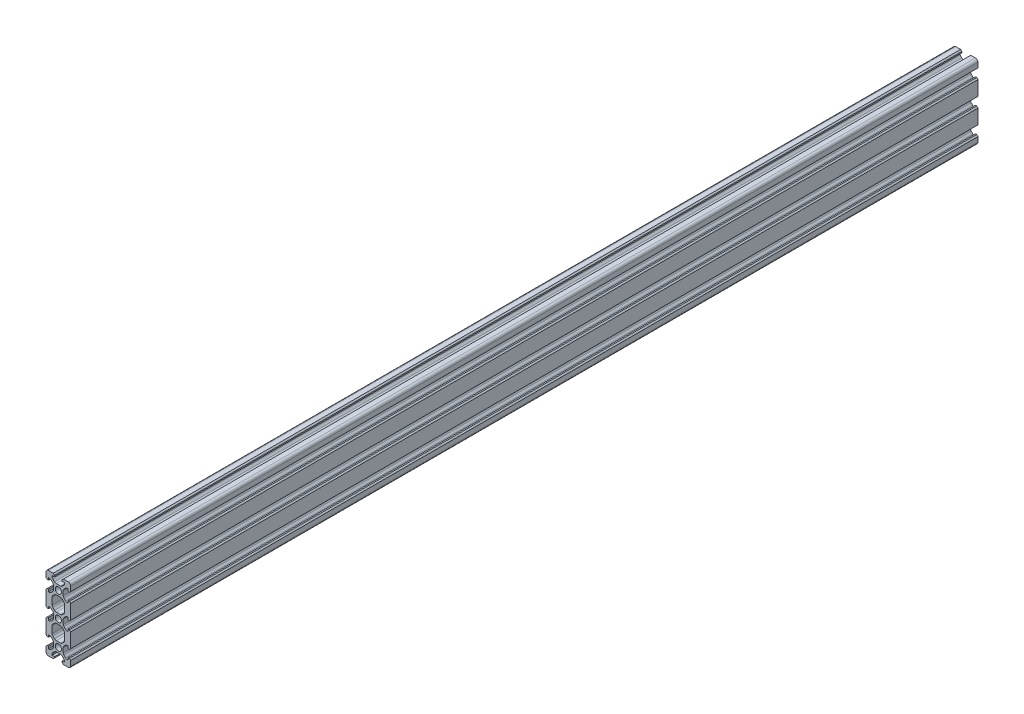
SolidWorks part; units mm, degrees
ref_plane "Front Plane" through (0, 0, 0) normal (0, 0, 1) x (1, 0, 0)
ref_plane "Top Plane" through (0, 0, 0) normal (0, 1, 0) x (1, 0, 0)
ref_plane "Right Plane" through (0, 0, 0) normal (1, 0, 0) x (0, 0, -1)
sketch "Sketch1" plane through (0, 0, 0) normal (0, 0, 1) x (1, 0, 0)
  line B0 (3.1, 29) -> (4.1, 30)
  line B1 (9, -23.1) -> (10, -24.1)
  line B2 (4.4142, -14.1716) -> (3.1236, -15.4621)
  line B3 (10, -15.9) -> (9, -16.9)
  line B4 (5.8284, -24.4142) -> (4.5379, -23.1236)
  line B5 (7.2426, -25) -> (8, -25)
  line B6 (8, -23.1) -> (8, -25)
  line B7 (7.2426, -15) -> (8, -15)
  line B8 (-1.7094, -16.0479) -> (1.7094, -16.0479)
  line B9 (8, -15) -> (8, -16.9)
  line B10 (8, -16.9) -> (9, -16.9)
  line B11 (8, -23.1) -> (9, -23.1)
  line B12 (3.9521, -18.2906) -> (3.9521, -21.7094)
  line B13 (-3.1236, -15.4621) -> (-4.4142, -14.1716)
  line B14 (10, -24.1) -> (10, -28)
  line B15 (4.5379, -16.8764) -> (5.8284, -15.5858)
  line B16 (-3.1, -29) -> (-4.1, -30)
  line B17 (8, -30) -> (4.1, -30)
  line B18 (4.1, -30) -> (3.1, -29)
  line B19 (-4.4142, -25.8284) -> (-3.1236, -24.5379)
  line B20 (-5, -27.2426) -> (-5, -28)
  line B21 (-3.1, -28) -> (-5, -28)
  line B22 (5, -27.2426) -> (5, -28)
  line B23 (5, -28) -> (3.1, -28)
  line B24 (3.1, -28) -> (3.1, -29)
  line B25 (-3.1, -28) -> (-3.1, -29)
  line B26 (1.7094, -23.9521) -> (-1.7094, -23.9521)
  line B27 (-4.1, -30) -> (-8, -30)
  line B28 (3.1236, -24.5379) -> (4.4142, -25.8284)
  line B29 (-9, -16.9) -> (-10, -15.9)
  line B30 (-10, -28) -> (-10, -24.1)
  line B31 (-10, -24.1) -> (-9, -23.1)
  line B32 (-5.8284, -15.5858) -> (-4.5379, -16.8764)
  line B33 (-7.2426, -15) -> (-8, -15)
  line B34 (-8, -16.9) -> (-8, -15)
  line B35 (-7.2426, -25) -> (-8, -25)
  line B36 (-8, -25) -> (-8, -23.1)
  line B37 (-8, -23.1) -> (-9, -23.1)
  line B38 (-8, -16.9) -> (-9, -16.9)
  line B39 (-3.9521, -21.7094) -> (-3.9521, -18.2906)
  line B40 (-4.5379, -23.1236) -> (-5.8284, -24.4142)
  circle B41 centre (0, -20) radius 2.5
  arc B42 (-4.5379, -16.8764) -> (-3.9521, -18.2906) centre (-5.9521, -18.2906) cw
  arc B43 (-5.8284, -15.5858) -> (-7.2426, -15) centre (-7.2426, -17) ccw
  arc B44 (-5, -12.7574) -> (-4.4142, -14.1716) centre (-3, -12.7574) ccw
  arc B45 (5, -12.7574) -> (4.4142, -14.1716) centre (3, -12.7574) cw
  arc B46 (7.2426, -15) -> (5.8284, -15.5858) centre (7.2426, -17) ccw
  arc B47 (5.8284, -24.4142) -> (7.2426, -25) centre (7.2426, -23) ccw
  arc B48 (5, -27.2426) -> (4.4142, -25.8284) centre (3, -27.2426) ccw
  arc B49 (-4.4142, -25.8284) -> (-5, -27.2426) centre (-3, -27.2426) ccw
  arc B50 (-7.2426, -25) -> (-5.8284, -24.4142) centre (-7.2426, -23) ccw
  arc B51 (-3.9521, -21.7094) -> (-4.5379, -23.1236) centre (-5.9521, -21.7094) cw
  arc B52 (-3.1236, -24.5379) -> (-1.7094, -23.9521) centre (-1.7094, -25.9521) cw
  arc B53 (1.7094, -23.9521) -> (3.1236, -24.5379) centre (1.7094, -25.9521) cw
  arc B54 (4.5379, -23.1236) -> (3.9521, -21.7094) centre (5.9521, -21.7094) cw
  arc B55 (3.9521, -18.2906) -> (4.5379, -16.8764) centre (5.9521, -18.2906) cw
  arc B56 (1.7094, -16.0479) -> (3.1236, -15.4621) centre (1.7094, -14.0479) ccw
  arc B57 (-1.7094, -16.0479) -> (-3.1236, -15.4621) centre (-1.7094, -14.0479) cw
  arc B58 (-8, -30) -> (-10, -28) centre (-8, -28) cw
  arc B59 (10, -28) -> (8, -30) centre (8, -28) cw
  line B60 (9, -3.1) -> (10, -4.1)
  line B61 (5, 7.2426) -> (5, 12.7574)
  line B62 (4.4142, 5.8284) -> (3.1236, 4.5379)
  line B63 (8, 5) -> (8, 3.1)
  line B64 (10, 15.9) -> (10, 4.1)
  line B65 (-10, -4.1) -> (-9, -3.1)
  line B66 (7.2426, -5) -> (8, -5)
  line B67 (8, -3.1) -> (9, -3.1)
  line B68 (-8, -3.1) -> (-9, -3.1)
  line B69 (10, 4.1) -> (9, 3.1)
  line B70 (-5, -7.2426) -> (-5, -12.7574)
  line B71 (-10, 4.1) -> (-10, 15.9)
  line B72 (-5, 7.2426) -> (-5, 12.7574)
  line B73 (3.1236, -4.5379) -> (4.4142, -5.8284)
  line B74 (-8, -5) -> (-8, -3.1)
  line B75 (-3.9521, -1.7094) -> (-3.9521, 1.7094)
  line B76 (8, 3.1) -> (9, 3.1)
  line B77 (-8, 3.1) -> (-8, 5)
  line B78 (8, -3.1) -> (8, -5)
  line B79 (1.7094, -3.9521) -> (-1.7094, -3.9521)
  line B80 (7.2426, 5) -> (8, 5)
  line B81 (10, -4.1) -> (10, -15.9)
  line B82 (-9, 3.1) -> (-10, 4.1)
  line B83 (4.5379, 3.1236) -> (5.8284, 4.4142)
  line B84 (-5.8284, 4.4142) -> (-4.5379, 3.1236)
  line B85 (3.9521, 1.7094) -> (3.9521, -1.7094)
  line B86 (-7.2426, 5) -> (-8, 5)
  line B87 (-1.7094, 3.9521) -> (1.7094, 3.9521)
  line B88 (-4.5379, -3.1236) -> (-5.8284, -4.4142)
  line B89 (-10, -15.9) -> (-10, -4.1)
  line B90 (-4.4142, -5.8284) -> (-3.1236, -4.5379)
  line B91 (5.8284, -4.4142) -> (4.5379, -3.1236)
  line B92 (-3.1236, 4.5379) -> (-4.4142, 5.8284)
  line B93 (5, -7.2426) -> (5, -12.7574)
  line B94 (-7.2426, -5) -> (-8, -5)
  line B95 (-8, 3.1) -> (-9, 3.1)
  arc B96 (1.7094, -3.9521) -> (3.1236, -4.5379) centre (1.7094, -5.9521) cw
  arc B97 (3.9521, 1.7094) -> (4.5379, 3.1236) centre (5.9521, 1.7094) cw
  arc B98 (4.5379, -3.1236) -> (3.9521, -1.7094) centre (5.9521, -1.7094) cw
  arc B99 (-4.4142, -5.8284) -> (-5, -7.2426) centre (-3, -7.2426) ccw
  arc B100 (-5, 7.2426) -> (-4.4142, 5.8284) centre (-3, 7.2426) ccw
  arc B101 (1.7094, 3.9521) -> (3.1236, 4.5379) centre (1.7094, 5.9521) ccw
  arc B102 (5, -7.2426) -> (4.4142, -5.8284) centre (3, -7.2426) ccw
  arc B103 (-7.2426, -5) -> (-5.8284, -4.4142) centre (-7.2426, -3) ccw
  arc B104 (5, 7.2426) -> (4.4142, 5.8284) centre (3, 7.2426) cw
  circle B105 centre (0, 0) radius 2.5
  arc B106 (-1.7094, 3.9521) -> (-3.1236, 4.5379) centre (-1.7094, 5.9521) cw
  arc B107 (-3.9521, -1.7094) -> (-4.5379, -3.1236) centre (-5.9521, -1.7094) cw
  arc B108 (-3.1236, -4.5379) -> (-1.7094, -3.9521) centre (-1.7094, -5.9521) cw
  arc B109 (-5.8284, 4.4142) -> (-7.2426, 5) centre (-7.2426, 3) ccw
  arc B110 (5.8284, -4.4142) -> (7.2426, -5) centre (7.2426, -3) ccw
  arc B111 (-4.5379, 3.1236) -> (-3.9521, 1.7094) centre (-5.9521, 1.7094) cw
  arc B112 (7.2426, 5) -> (5.8284, 4.4142) centre (7.2426, 3) ccw
  line B113 (8, 25) -> (8, 23.1)
  line B114 (3.9521, 21.7094) -> (3.9521, 18.2906)
  line B115 (-4.1, 30) -> (-3.1, 29)
  line B116 (-5, 27.2426) -> (-5, 28)
  line B117 (-5.8284, 24.4142) -> (-4.5379, 23.1236)
  line B118 (8, 16.9) -> (9, 16.9)
  line B119 (3.1, 28) -> (3.1, 29)
  line B120 (1.7094, 16.0479) -> (-1.7094, 16.0479)
  line B121 (-8, 16.9) -> (-9, 16.9)
  line B122 (-3.1236, 24.5379) -> (-4.4142, 25.8284)
  line B123 (3.1, 28) -> (5, 28)
  line B124 (-8, 23.1) -> (-8, 25)
  line B125 (8, 16.9) -> (8, 15)
  line B126 (-10, 15.9) -> (-9, 16.9)
  line B127 (-3.1, 28) -> (-3.1, 29)
  line B128 (3.1236, 15.4621) -> (4.4142, 14.1716)
  line B129 (5.8284, 15.5858) -> (4.5379, 16.8764)
  line B130 (10, 28) -> (10, 24.1)
  line B131 (-8, 15) -> (-8, 16.9)
  line B132 (7.2426, 25) -> (8, 25)
  line B133 (-5, 28) -> (-3.1, 28)
  line B134 (5, 27.2426) -> (5, 28)
  line B135 (-7.2426, 15) -> (-8, 15)
  line B136 (9, 16.9) -> (10, 15.9)
  line B137 (-9, 23.1) -> (-10, 24.1)
  line B138 (4.5379, 23.1236) -> (5.8284, 24.4142)
  line B139 (-4.4142, 14.1716) -> (-3.1236, 15.4621)
  line B140 (4.4142, 25.8284) -> (3.1236, 24.5379)
  line B141 (-3.9521, 18.2906) -> (-3.9521, 21.7094)
  line B142 (4.1, 30) -> (8, 30)
  line B143 (-8, 30) -> (-4.1, 30)
  line B144 (10, 24.1) -> (9, 23.1)
  line B145 (-1.7094, 23.9521) -> (1.7094, 23.9521)
  line B146 (7.2426, 15) -> (8, 15)
  line B147 (-10, 24.1) -> (-10, 28)
  line B148 (-7.2426, 25) -> (-8, 25)
  line B149 (-8, 23.1) -> (-9, 23.1)
  line B150 (8, 23.1) -> (9, 23.1)
  line B151 (-4.5379, 16.8764) -> (-5.8284, 15.5858)
  arc B152 (-5, 27.2426) -> (-4.4142, 25.8284) centre (-3, 27.2426) ccw
  arc B153 (-7.2426, 15) -> (-5.8284, 15.5858) centre (-7.2426, 17) ccw
  arc B154 (1.7094, 16.0479) -> (3.1236, 15.4621) centre (1.7094, 14.0479) cw
  arc B155 (-4.4142, 14.1716) -> (-5, 12.7574) centre (-3, 12.7574) ccw
  arc B156 (1.7094, 23.9521) -> (3.1236, 24.5379) centre (1.7094, 25.9521) ccw
  circle B157 centre (0, 20) radius 2.5
  arc B158 (-10, 28) -> (-8, 30) centre (-8, 28) cw
  arc B159 (4.5379, 16.8764) -> (3.9521, 18.2906) centre (5.9521, 18.2906) cw
  arc B160 (-3.1236, 15.4621) -> (-1.7094, 16.0479) centre (-1.7094, 14.0479) cw
  arc B161 (5, 27.2426) -> (4.4142, 25.8284) centre (3, 27.2426) cw
  arc B162 (5, 12.7574) -> (4.4142, 14.1716) centre (3, 12.7574) ccw
  arc B163 (-4.5379, 23.1236) -> (-3.9521, 21.7094) centre (-5.9521, 21.7094) cw
  arc B164 (8, 30) -> (10, 28) centre (8, 28) cw
  arc B165 (-3.9521, 18.2906) -> (-4.5379, 16.8764) centre (-5.9521, 18.2906) cw
  arc B166 (3.9521, 21.7094) -> (4.5379, 23.1236) centre (5.9521, 21.7094) cw
  arc B167 (-5.8284, 24.4142) -> (-7.2426, 25) centre (-7.2426, 23) ccw
  arc B168 (-1.7094, 23.9521) -> (-3.1236, 24.5379) centre (-1.7094, 25.9521) cw
  arc B169 (5.8284, 15.5858) -> (7.2426, 15) centre (7.2426, 17) ccw
  arc B170 (7.2426, 25) -> (5.8284, 24.4142) centre (7.2426, 23) ccw
sketch_block_instance "2060-1"
sketch_block "2060" parameters "D1"=2, "D2"=2, "D3"=2
extrude "Boss-Extrude1" add sketch "Sketch1" along normal blind 735
